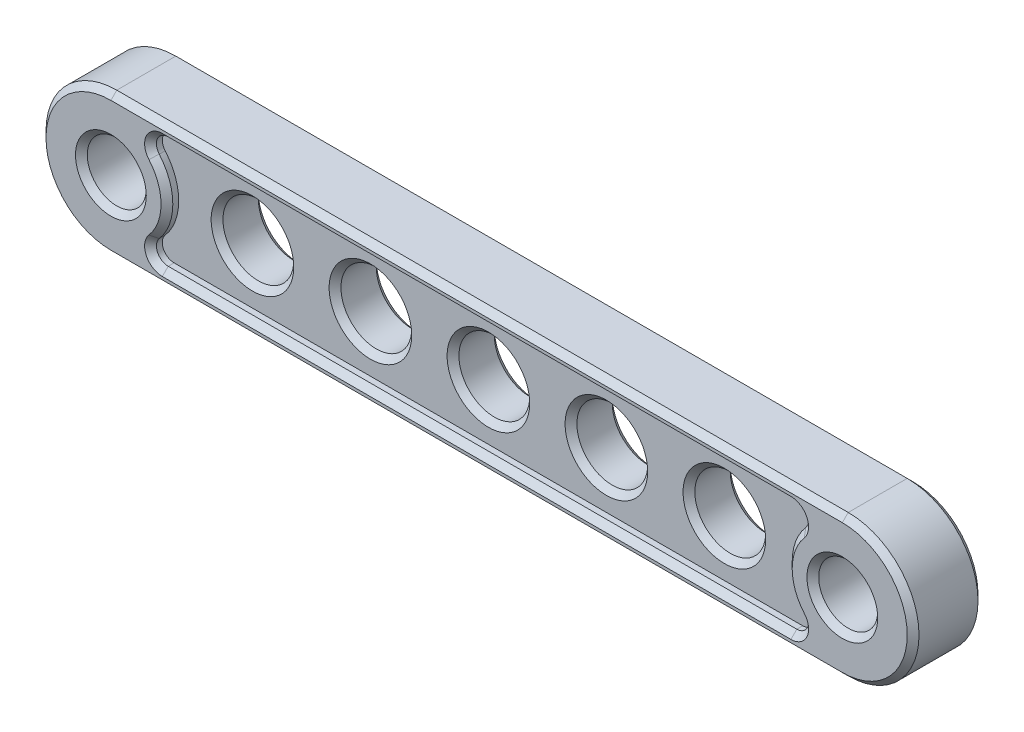
SolidWorks part; units mm, degrees
ref_plane "Front Plane" through (0, 0, 0) normal (0, 0, 1) x (1, 0, 0)
ref_plane "Top Plane" through (0, 0, 0) normal (0, 1, 0) x (1, 0, 0)
ref_plane "Right Plane" through (0, 0, 0) normal (1, 0, 0) x (0, 0, -1)
sketch "Sketch1" plane through (0, 0, 0) normal (0, 0, 1) x (1, 0, 0)
  line L0 (-31, 0) -> (31, 0) construction
  line L1 (-31, 6) -> (31, 6)
  line L2 (-31, -6) -> (31, -6)
  arc A0 (-31, 6) -> (-31, -6) centre (-31, 0) ccw
  arc A1 (31, -6) -> (31, 6) centre (31, 0) ccw
  circle A2 centre (-31, 0) radius 2.5
  circle A3 centre (31, 0) radius 2.5
  point P2 (0, 0)
  dimension "D2" = 6
  dimension "D3" = 5
  dimension "D4" = 5
  dimension "D1" = 62
extrude "Boss-Extrude1" add sketch "Sketch1" along normal mid plane 6
sketch "Sketch2" plane through (0, 0, 3) normal (0, 0, 1) x (1, 0, 0)
  line L0 (-26.6411, 4.75) -> (26.6411, 4.75)
  line L1 (-26.6411, -4.75) -> (26.6411, -4.75)
  arc A0 (-27.3992, -3.0978) -> (-27.3992, 3.0978) centre (-31, 0) ccw
  arc A1 (27.3992, 3.0978) -> (27.3992, -3.0978) centre (31, 0) ccw
  arc A2 (26.6411, -4.75) -> (27.3992, -3.0978) centre (26.6411, -3.75) ccw
  arc A3 (26.6411, 4.75) -> (27.3992, 3.0978) centre (26.6411, 3.75) cw
  arc A4 (-27.3992, -3.0978) -> (-26.6411, -4.75) centre (-26.6411, -3.75) ccw
  arc A5 (-27.3992, 3.0978) -> (-26.6411, 4.75) centre (-26.6411, 3.75) cw
  point P14 (-31, -4.75)
  point P17 (-31, 4.75)
  dimension "D1" = 9.5
  dimension "D2" = 9.5
  dimension "D3" = 1
extrude "Cut-Extrude1" cut sketch "Sketch2" against normal blind 1
mirror "Mirror1" about plane through (0, 0, 0) normal (0, 0, 1) of "Cut-Extrude1"
sketch "Sketch3" plane through (0, 0, 2) normal (0, 0, 1) x (1, 0, 0)
  line L0 (-31, 0) -> (31, 0) construction
  circle A0 centre (0, 0) radius 3
  circle A2 centre (-20, 0) radius 3
  circle A3 centre (-10, 0) radius 3
  circle A4 centre (10, 0) radius 3
  circle A5 centre (20, 0) radius 3
  dimension "D1" = 6
  dimension "D2" = 11
  dimension "D3" = 10
  dimension "D4" = 10
  dimension "D5" = 11
extrude "Cut-Extrude2" cut sketch "Sketch3" against normal through all
chamfer "Chamfer1" distance 0.5 angle 45 19 edges at (26.25, 0, 3) (27.55, 4.167, 3) (0, 4.75, 3) (-27.55, 4.167, 3) (-26.25, 0, 3) (-27.55, -4.167, 3) (0, -4.75, 3) (27.55, -4.167, 3) (-28.5, 0, 3) (0, 6, 3) (37, 0, 3) (0, -6, 3) (-37, 0, 3) (33.5, 0, 3) (23, 0, 2) (13, 0, 2) (3, 0, 2) (-7, 0, 2) (-17, 0, 2)
chamfer "Chamfer2" distance 0.5 angle 45 19 edges at (0, -4.75, -3) (-27.55, -4.167, -3) (-26.25, 0, -3) (-27.55, 4.167, -3) (0, 4.75, -3) (27.55, 4.167, -3) (26.25, 0, -3) (27.55, -4.167, -3) (0, -6, -3) (37, 0, -3) (0, 6, -3) (-37, 0, -3) (-28.5, 0, -3) (33.5, 0, -3) (-23, 0, -2) (-13, 0, -2) (-3, 0, -2) (7, 0, -2) (17, 0, -2)
